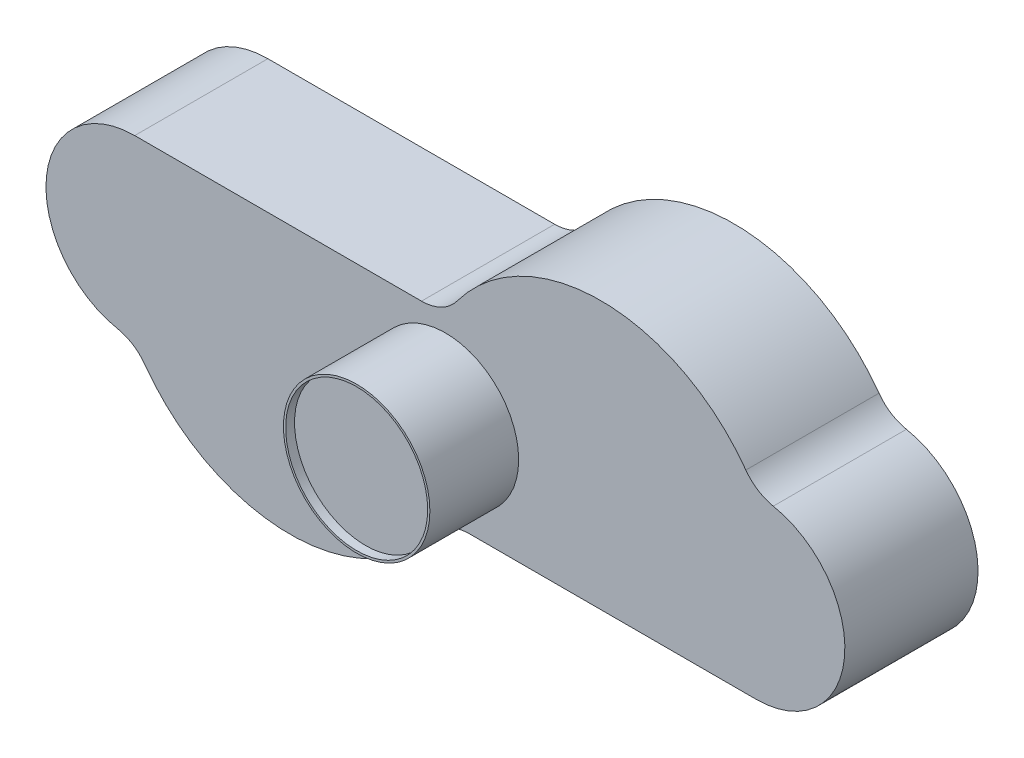
SolidWorks part; units mm, degrees
ref_plane "Front Plane" through (0, 0, 0) normal (0, 0, 1) x (1, 0, 0)
ref_plane "Top Plane" through (0, 0, 0) normal (0, 1, 0) x (1, 0, 0)
ref_plane "Right Plane" through (0, 0, 0) normal (1, 0, 0) x (0, 0, -1)
sketch "Sketch1" plane through (0, 0, 0) normal (0, 0, 1) x (1, 0, 0)
  line L0 (0, 0) -> (70, 0) construction
  line L1 (0, 10) -> (70, 10)
  line L2 (0, -10) -> (70, -10)
  line L3 (0, 10) -> (35, 10)
  line L4 (35, -10) -> (70, -10)
  arc A0 (0, 10) -> (0, -10) centre (0, 0) ccw
  arc A1 (70, -10) -> (70, 10) centre (70, 0) ccw
  arc A2 (35, 10) -> (70, 10) centre (52.5, 0) cw
  arc A3 (0, -10) -> (35, -10) centre (17.5, 0) ccw
  point P3 (35, 0)
  dimension "D1" = 70
  dimension "D2" = 20
extrude "Boss-Extrude5" add sketch "Sketch1" along normal blind 15
sketch "Sketch5" plane through (0, 0, 15) normal (0, 0, 1) x (1, 0, 0)
  circle A0 centre (35, 0) radius 8.25
  dimension "D1" = 16.5
extrude "Boss-Extrude6" add sketch "Sketch5" along normal blind 10
sketch "Sketch6" plane through (0, 0, 25) normal (0, 0, 1) x (1, 0, 0)
  circle A0 centre (35, 0) radius 8
  dimension "D1" = 16
extrude "Cut-Extrude2" cut sketch "Sketch6" against normal blind 1
fillet "Fillet3" radius 5 4 edges at (0, -10, 7.5) (35, -10, 7.5) (70, 10, 7.5) (35, 10, 7.5)
